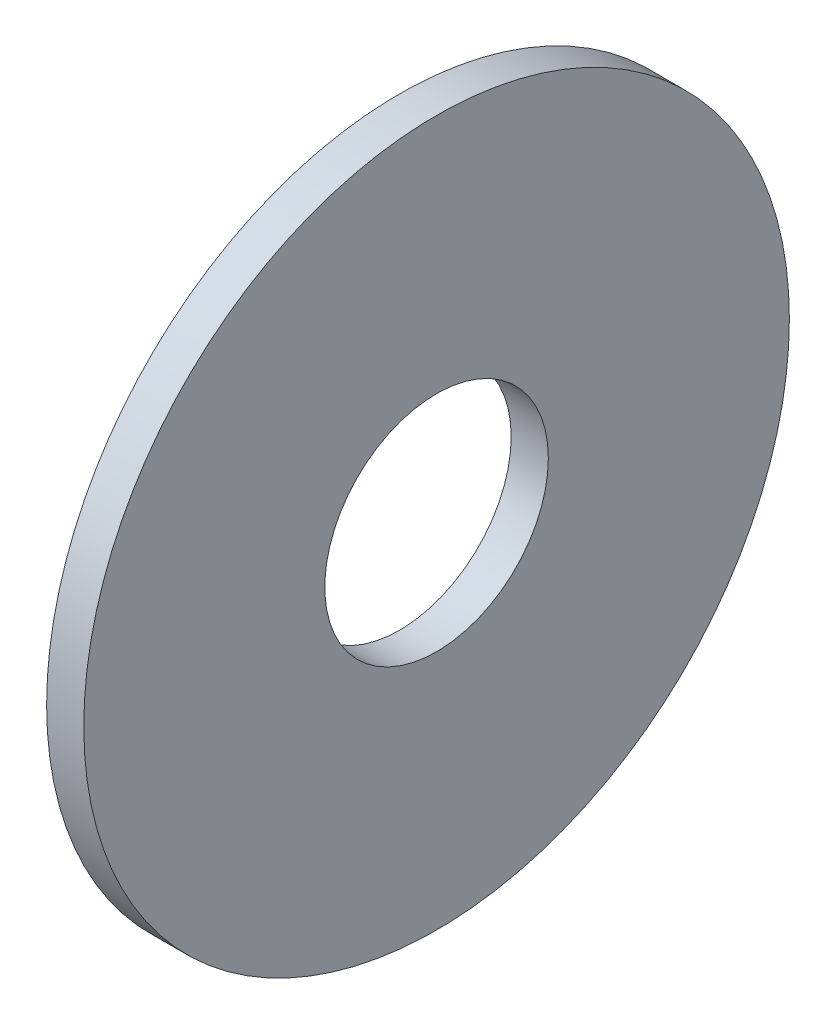
SolidWorks part; units mm, degrees
ref_plane "Front Plane" through (0, 0, 0) normal (0, 0, 1) x (1, 0, 0)
ref_plane "Top Plane" through (0, 0, 0) normal (0, 1, 0) x (1, 0, 0)
ref_plane "Right Plane" through (0, 0, 0) normal (1, 0, 0) x (0, 0, -1)
sketch "Sketch1" plane through (0, 0, 0) normal (1, 0, 0) x (0, 0, -1)
  circle A0 centre (0, 0) radius 9.5
  circle A1 centre (0, 0) radius 3 construction
  circle A2 centre (0, 0) radius 3.01
  dimension "OD" = 19
  dimension "For Shaft Diameter" = 6
  dimension "ID" = 6.02
sketch "Sketch2" plane through (0, 0, 0) normal (0, 0, 1) x (1, 0, 0)
  line L0 (0.5, 0) -> (-0.5, 0) construction
  line L1 (0.5, -9.5) -> (-0.5, -9.5) construction
  line L2 (0.5, -9.5) -> (0.5, 9.5) construction
  line L3 (0.5, 9.5) -> (-0.5, 9.5) construction
  line L4 (-0.5, -9.5) -> (-0.5, 9.5) construction
  point P6 (0, 9.5)
  point P9 (0, -9.5)
  dimension "Thickness" = 1
sketch "Sketch3" plane through (0, 0, 0) normal (1, 0, 0) x (0, 0, -1)
  circle A1 centre (0, 0) radius 9.5 construction
  circle A3 centre (0, 0) radius 9.5
  circle A4 centre (0, 0) radius 3.01 construction
  circle A5 centre (0, 0) radius 3.01
extrude "Boss-Extrude1" add sketch "Sketch3" along normal up to vertex (0.5 mm away) and the other way up to vertex (0.5 mm away) up to point (0.5, 9.5, 0) other way up to point (-0.5, 9.5, 0)
